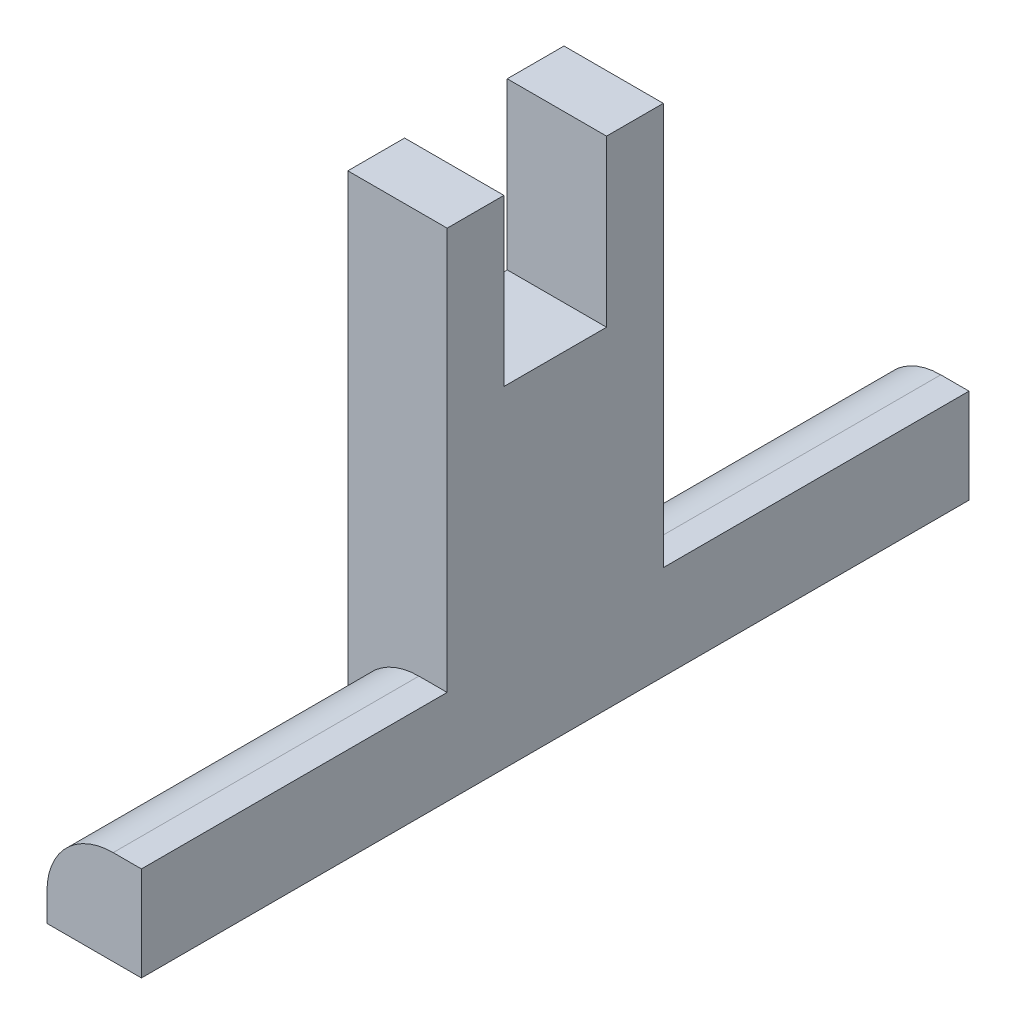
SolidWorks part; units mm, degrees
ref_plane "Front Plane" through (0, 0, 0) normal (0, 0, 1) x (1, 0, 0)
ref_plane "Top Plane" through (0, 0, 0) normal (0, 1, 0) x (1, 0, 0)
ref_plane "Right Plane" through (0, 0, 0) normal (1, 0, 0) x (0, 0, -1)
sketch "Sketch1" plane through (0, 0, 0) normal (1, 0, 0) x (0, 0, -1)
  line L0 (-3.1, 10) -> (-3.1, 0)
  line L1 (-3.1, 0) -> (-6.5301, 0)
  line L2 (-6.5301, 0) -> (-6.5301, 10)
  line L3 (-6.5301, 0) -> (-6.5301, -20)
  line L4 (-6.5301, -20) -> (6.5301, -20)
  line L5 (0, 0) -> (0, 50000) construction
  line L6 (6.5301, -20) -> (6.5301, 0)
  line L8 (6.5301, 0) -> (6.5301, 10)
  line L9 (3.1, 0) -> (6.5301, 0)
  line L10 (3.1, 10) -> (3.1, 0)
  line L11 (-3.1, 10) -> (3.1, 10)
  line L25 (6.5301, 10) -> (6.5301, 0.9112)
  line L26 (-6.5301, 10) -> (-6.5301, 0.9112)
  line L27 (-6.5301, 10) -> (-3.1, 10)
  line L28 (3.1, 10) -> (6.5301, 10)
  line L29 (3.1, 0) -> (-3.1, 0)
  line L35 (-25, 12.1535) -> (-25, -1.9655) construction
  line L36 (25, 12.1535) -> (25, -1.9655) construction
  dimension "D3" = 20
  dimension "D1" = 6.2
  dimension "D2" = 10
  dimension "D4" = 25
extrude "Boss-Extrude2" add sketch "Sketch1" against normal blind 6
sketch "Sketch2" plane through (0, 0, 6.5301) normal (0, 0, 1) x (1, 0, 0)
  line L1 (0, -20) -> (-5.7072, -20)
  line L2 (0, -20) -> (0, -14.2928)
  line L3 (0, -14.2928) -> (-1.7072, -14.2928)
  line L4 (-5.7072, -20) -> (-5.7072, -18.2928)
  arc A0 (-5.7072, -18.2928) -> (-1.7072, -14.2928) centre (-1.7072, -18.2928) cw
  dimension "D1" = 4
  dimension "D2" = 5.7072
extrude "Boss-Extrude3" add sketch "Sketch2" along normal up to vertex (18.4699 mm away) and the other way up to vertex (31.5301 mm away) up to point (0, -1.9655, 25) other way up to point (0, -1.9655, -25)
